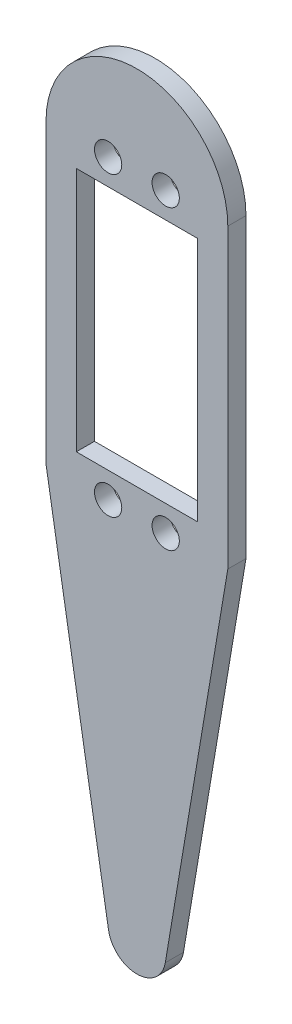
SolidWorks part; units mm, degrees
material "Acrylic (Medium-high impact)"
ref_plane "Front Plane" through (0, 0, 0) normal (0, 0, 1) x (1, 0, 0)
ref_plane "Top Plane" through (0, 0, 0) normal (0, 1, 0) x (1, 0, 0)
ref_plane "Right Plane" through (0, 0, 0) normal (1, 0, 0) x (0, 0, -1)
sketch "Sketch1" plane through (0, 0, 0) normal (0, 0, 1) x (1, 0, 0)
  line L0 (-5, -1011.6385) -> (-5, 48988.3615) construction
  line L1 (0, 0) -> (20, 0)
  line L2 (0, 0) -> (0, 40.5)
  line L3 (0, 40.5) -> (20, 40.5)
  line L4 (20, 0) -> (20, 40.5)
  line L5 (10, -959.5) -> (10, 49040.5) construction
  line L6 (5.25, -1016.8654) -> (5.25, -65.2861) construction
  line L7 (14.75, -1019.8958) -> (14.75, 48980.1042) construction
  line L8 (25, -978.4803) -> (25, 49021.5197) construction
  line L9 (-979.0853, 44.75) -> (49020.9147, 44.75) construction
  line L10 (-999.9631, -4.25) -> (49000.0369, -4.25) construction
  line L11 (-5, 44.75) -> (-5, -4.25)
  line L12 (25, 44.75) -> (25, -4.25)
  line L13 (-1010.4081, 30.36) -> (48989.5919, 30.36) construction
  line L14 (-990, -69.64) -> (49010, -69.64) construction
  line L15 (-5, -4.25) -> (5.3156, -65.6767)
  line L16 (25, -4.25) -> (14.6844, -65.6767)
  line L17 (5.25, -6.5) -> (5.25, 48983.1346) construction
  circle A0 centre (14.75, -4.25) radius 2.25
  circle A1 centre (5.25, -4.25) radius 2.25
  circle A2 centre (14.75, 44.75) radius 2.25
  circle A3 centre (5.25, 44.75) radius 2.25
  arc A4 (25, 44.75) -> (-5, 44.75) centre (10, 44.75) ccw
  arc A5 (5.3156, -65.6767) -> (14.6844, -65.6767) centre (10, -64.89) ccw
  point P10 (10, 40.5)
  dimension "D8" = 4.5
  dimension "D9" = 4.5
  dimension "D10" = 4.5
  dimension "D11" = 4.5
  dimension "D12" = 40.5
  dimension "D15" = 4.75
  dimension "D1" = 10
  dimension "D2" = 4.75
  dimension "D3" = 4.75
  dimension "D4" = 4.25
  dimension "D5" = 10.14
  dimension "D6" = 5
  dimension "D7" = 4.25
  dimension "D13" = 49
  dimension "D14" = 100
extrude "Boss-Extrude1" add sketch "Sketch1" along normal blind 3
